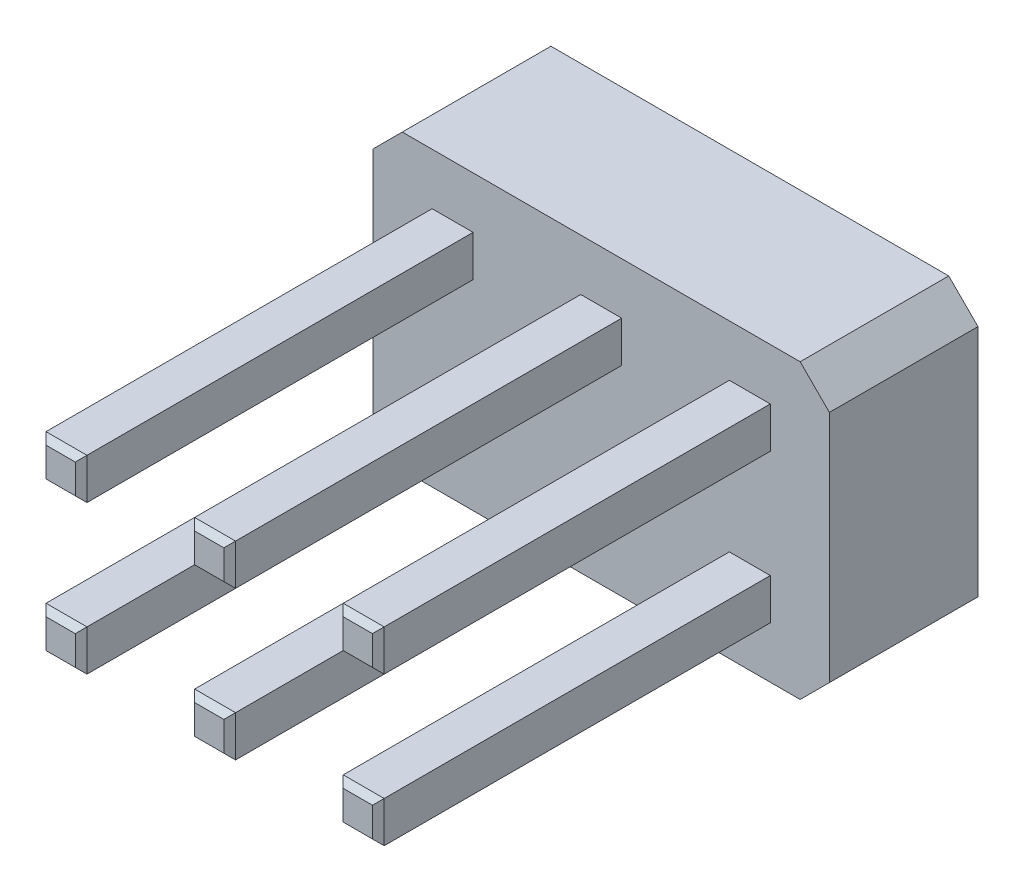
SolidWorks part; units mm, degrees
ref_plane "Front Plane" through (0, 0, 0) normal (0, 0, 1) x (1, 0, 0)
ref_plane "Top Plane" through (0, 0, 0) normal (0, 1, 0) x (1, 0, 0)
ref_plane "Right Plane" through (0, 0, 0) normal (1, 0, 0) x (0, 0, -1)
sketch "Sketch1" plane through (0, 0, 0) normal (0, 0, 1) x (1, 0, 0)
  line L1 (-3.9, 2.5) -> (3.9, 2.5)
  line L2 (-3.9, 2.5) -> (-3.9, -2.5)
  line L3 (-3.9, -2.5) -> (3.9, -2.5)
  line L4 (3.9, 2.5) -> (3.9, -2.5)
  line L5 (-3.9, 2.5) -> (3.9, -2.5) construction
  line L6 (-3.9, -2.5) -> (3.9, 2.5) construction
  point P0 (0, 0)
  dimension "D1" = 5
  dimension "D2" = 7.8
extrude "Boss-Extrude1" add sketch "Sketch1" along normal blind 2.54
sketch "Sketch2" plane through (0, 0, 2.54) normal (0, 0, 1) x (1, 0, 0)
  line L0 (-0.35, 1.62) -> (0.35, 1.62)
  line L1 (-2.89, 1.62) -> (-2.19, 1.62)
  line L2 (-2.89, 1.62) -> (-2.89, 0.92)
  line L3 (-2.89, 0.92) -> (-2.19, 0.92)
  line L4 (-2.19, 1.62) -> (-2.19, 0.92)
  line L5 (0.35, 1.62) -> (0.35, 0.92)
  line L6 (-0.35, 0.92) -> (0.35, 0.92)
  line L7 (-0.35, 1.62) -> (-0.35, 0.92)
  line L8 (2.19, 1.62) -> (2.89, 1.62)
  line L9 (2.89, 1.62) -> (2.89, 0.92)
  line L10 (2.19, 0.92) -> (2.89, 0.92)
  line L11 (2.19, 1.62) -> (2.19, 0.92)
  line L12 (-0.35, -0.92) -> (0.35, -0.92)
  line L13 (0.35, -0.92) -> (0.35, -1.62)
  line L14 (-0.35, -1.62) -> (0.35, -1.62)
  line L15 (-0.35, -0.92) -> (-0.35, -1.62)
  line L16 (2.19, -0.92) -> (2.89, -0.92)
  line L17 (2.89, -0.92) -> (2.89, -1.62)
  line L18 (2.19, -1.62) -> (2.89, -1.62)
  line L19 (2.19, -0.92) -> (2.19, -1.62)
  line L20 (-2.89, -0.92) -> (-2.19, -0.92)
  line L21 (-2.19, -0.92) -> (-2.19, -1.62)
  line L22 (-2.89, -1.62) -> (-2.19, -1.62)
  line L23 (-2.89, -0.92) -> (-2.89, -1.62)
  line L24 (0, 0) -> (0, 0.92) construction
  point P5 (-0.35, 1.27)
  point P28 (0, 0)
  point P29 (0, 0)
  point P30 (0, 0)
  dimension "D1" = 0.7
  dimension "D4" = 1.27
  dimension "D5" = 2.54
  dimension "D6" = 2.54
  dimension "D3" = 3
  dimension "D2" = 2
extrude "Boss-Extrude2" add sketch "Sketch2" along normal blind 6.7
chamfer "Chamfer1" distance 0.5 angle 45 4 edges at (3.9, 2.5, 1.27) (3.9, -2.5, 1.27) (-3.9, 2.5, 1.27) (-3.9, -2.5, 1.27)
chamfer "Chamfer2" distance 0.1 angle 45 24 edges at (2.54, 1.62, 9.24) (2.89, 1.27, 9.24) (2.54, 0.92, 9.24) (2.19, 1.27, 9.24) (0, 1.62, 9.24) (0.35, 1.27, 9.24) (0, 0.92, 9.24) (-0.35, 1.27, 9.24) (-2.54, 1.62, 9.24) (-2.19, 1.27, 9.24) (-2.54, 0.92, 9.24) (-2.89, 1.27, 9.24) (-2.54, -0.92, 9.24) (-2.19, -1.27, 9.24) (-2.54, -1.62, 9.24) (-2.89, -1.27, 9.24) (0, -0.92, 9.24) (0.35, -1.27, 9.24) (0, -1.62, 9.24) (-0.35, -1.27, 9.24) (2.54, -0.92, 9.24) (2.89, -1.27, 9.24) (2.54, -1.62, 9.24) (2.19, -1.27, 9.24)
